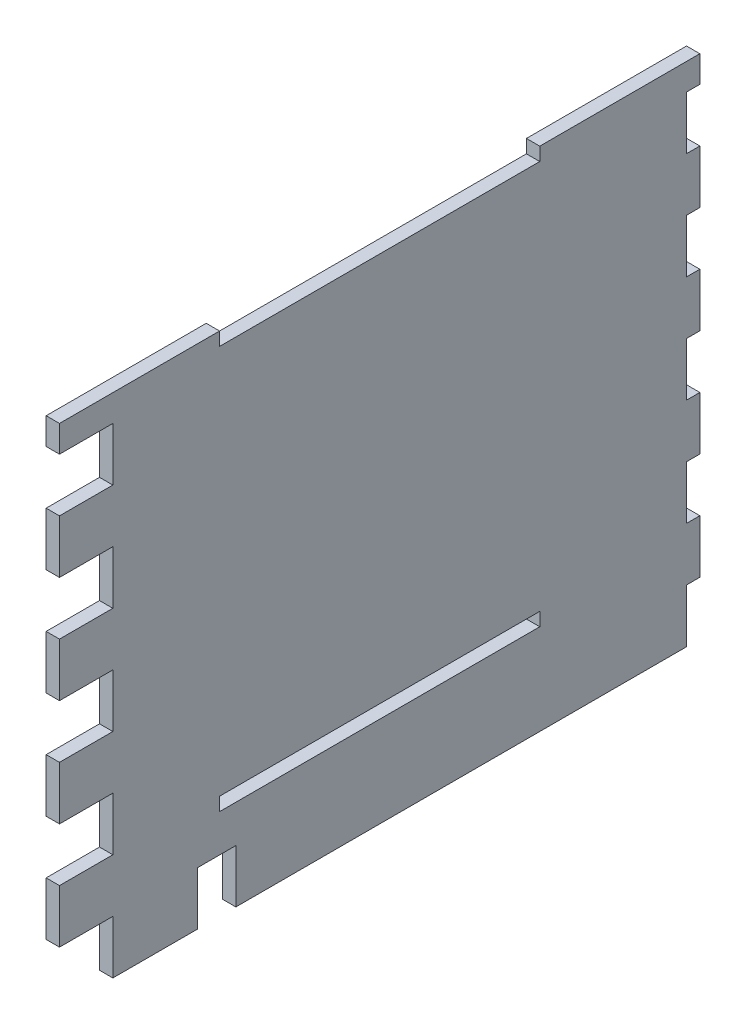
SolidWorks part; units mm, degrees
ref_plane "Front Plane" through (0, 0, 0) normal (0, 0, 1) x (1, 0, 0)
ref_plane "Top Plane" through (0, 0, 0) normal (0, 1, 0) x (1, 0, 0)
ref_plane "Right Plane" through (0, 0, 0) normal (1, 0, 0) x (0, 0, -1)
other "big teeth cut"
sketch "Sketch1" plane through (0, 0, 0) normal (1, 0, 0) x (0, 0, -1)
  line L25 (-326.0788, 150.6225) -> (-21.2788, 150.6225)
  line L26 (-326.0788, 150.6225) -> (-326.0788, -90.6775)
  line L27 (-326.0788, -90.6775) -> (-21.2788, -90.6775)
  line L28 (-21.2788, 150.6225) -> (-21.2788, -90.6775)
  dimension "D1" = 241.3
  dimension "D2" = 304.8
extrude "Boss-Extrude4" add sketch "Sketch1" along normal blind 6.35
sketch "big teeth" plane through (6.35, 0, 0) normal (1, 0, 0) x (0, 0, -1)
  line L0 (-326.0788, 150.6225) -> (-326.0788, -90.6775) construction
  line L1 (-326.0788, -90.6775) -> (-300.6788, -90.6775)
  line L2 (-326.0788, -90.6775) -> (-326.0788, -65.2775)
  line L3 (-326.0788, -65.2775) -> (-300.6788, -65.2775)
  line L4 (-300.6788, -90.6775) -> (-300.6788, -65.2775)
  line L5 (-326.0788, -39.8775) -> (-300.6788, -39.8775)
  line L6 (-326.0788, -39.8775) -> (-326.0788, -14.4775)
  line L7 (-326.0788, -14.4775) -> (-300.6788, -14.4775)
  line L8 (-300.6788, -39.8775) -> (-300.6788, -14.4775)
  line L10 (-326.0788, 10.9225) -> (-300.6788, 10.9225)
  line L11 (-326.0788, 10.9225) -> (-326.0788, 36.3225)
  line L12 (-326.0788, 36.3225) -> (-300.6788, 36.3225)
  line L13 (-300.6788, 10.9225) -> (-300.6788, 36.3225)
  line L14 (-326.0788, 61.7225) -> (-300.6788, 61.7225)
  line L15 (-326.0788, 61.7225) -> (-326.0788, 87.1225)
  line L16 (-326.0788, 87.1225) -> (-300.6788, 87.1225)
  line L17 (-300.6788, 61.7225) -> (-300.6788, 87.1225)
  line L18 (-326.0788, 112.5225) -> (-300.6788, 112.5225)
  line L19 (-326.0788, 112.5225) -> (-326.0788, 137.9225)
  line L20 (-326.0788, 137.9225) -> (-300.6788, 137.9225)
  line L21 (-300.6788, 112.5225) -> (-300.6788, 137.9225)
  dimension "D1" = 25.4
  dimension "D2" = 25.4
  dimension "D3" = 25.4
  dimension "D4" = 25.4
  dimension "D5" = 25.4
  dimension "D6" = 25.4
  dimension "D7" = 25.4
  dimension "D8" = 25.4
  dimension "D9" = 25.4
  dimension "D10" = 25.4
  dimension "D11" = 25.4
  dimension "D12" = 25.4
  dimension "D13" = 25.4
sketch "Sketch3" plane through (0, 0, 0) normal (-1, 0, 0) x (0, 0, 1)
  line L1 (21.2788, -90.6775) -> (27.6288, -90.6775)
  line L2 (21.2788, -90.6775) -> (21.2788, -65.207)
  line L3 (21.2788, -65.207) -> (27.6288, -65.207)
  line L4 (27.6288, -90.6775) -> (27.6288, -65.207)
  line L9 (21.2788, -90.6775) -> (21.2788, 150.6225) construction
  line L22 (21.2788, -39.807) -> (27.6288, -39.807)
  line L23 (21.2788, -39.807) -> (21.2788, -14.407)
  line L24 (21.2788, -14.407) -> (27.6288, -14.407)
  line L25 (27.6288, -39.807) -> (27.6288, -14.407)
  line L27 (21.2788, 10.993) -> (27.6288, 10.993)
  line L28 (21.2788, 10.993) -> (21.2788, 36.393)
  line L29 (21.2788, 36.393) -> (27.6288, 36.393)
  line L30 (27.6288, 10.993) -> (27.6288, 36.393)
  line L31 (21.2788, 61.793) -> (27.6288, 61.793)
  line L32 (21.2788, 61.793) -> (21.2788, 87.193)
  line L33 (21.2788, 87.193) -> (27.6288, 87.193)
  line L34 (27.6288, 61.793) -> (27.6288, 87.193)
  line L35 (21.2788, 112.593) -> (27.6288, 112.593)
  line L36 (21.2788, 112.593) -> (21.2788, 137.993)
  line L37 (21.2788, 137.993) -> (27.6288, 137.993)
  line L38 (27.6288, 112.593) -> (27.6288, 137.993)
  dimension "D1" = 6.35
  dimension "D2" = 25.4
  dimension "D3" = 25.4
  dimension "D4" = 25.4
  dimension "D5" = 25.4
  dimension "D6" = 25.4
  dimension "D7" = 25.4
  dimension "D8" = 25.4
  dimension "D9" = 6.35
  dimension "D10" = 25.4
extrude "Small_teeth_cut" cut sketch "Sketch3" against normal blind 7.62
extrude "Big_teeth_cut" cut sketch "big teeth" against normal through all both and the other way through all
sketch "Sketch4" plane through (6.35, 0, 0) normal (1, 0, 0) x (0, 0, -1)
  line L0 (-21.2788, 150.6225) -> (-326.0788, 150.6225) construction
  line L1 (-249.8788, 150.6225) -> (-97.4788, 150.6225)
  line L2 (-249.8788, 150.6225) -> (-249.8788, 144.2725)
  line L3 (-249.8788, 144.2725) -> (-97.4788, 144.2725)
  line L4 (-97.4788, 150.6225) -> (-97.4788, 144.2725)
  line L7 (-21.2788, 137.993) -> (-21.2788, 150.6225) construction
  point P6 (-97.4788, 147.4475)
  dimension "D1" = 152.4
  dimension "D2" = 76.2
  dimension "D3" = 6.35
extrude "Cut-Extrude1" cut sketch "Sketch4" against normal through all
sketch "Sketch5" plane through (0, 0, 0) normal (-1, 0, 0) x (0, 0, 1)
  line L1 (242.1324, -65.3617) -> (260.498, -65.3617)
  line L2 (242.1324, -65.3617) -> (242.1324, -90.6775)
  line L3 (242.1324, -90.6775) -> (260.498, -90.6775)
  line L4 (260.498, -65.3617) -> (260.498, -90.6775)
  line L5 (300.6788, -90.6775) -> (27.6288, -90.6775) construction
extrude "Cut-Extrude2" cut sketch "Sketch5" against normal through all
sketch "Sketch6" plane through (0, 0, 0) normal (-1, 0, 0) x (0, 0, 1)
  line L0 (242.1324, -90.6775) -> (27.6288, -90.6775) construction
  line L1 (97.4788, -41.1475) -> (249.8788, -41.1475)
  line L2 (97.4788, -41.1475) -> (97.4788, -47.4975)
  line L3 (97.4788, -47.4975) -> (249.8788, -47.4975)
  line L4 (249.8788, -41.1475) -> (249.8788, -47.4975)
  line L5 (21.2788, -65.207) -> (21.2788, -39.807) construction
  dimension "D1" = 43.18
  dimension "D2" = 6.35
  dimension "D3" = 152.4
  dimension "D4" = 76.2
extrude "Cut-Extrude3" cut sketch "Sketch6" against normal through all
